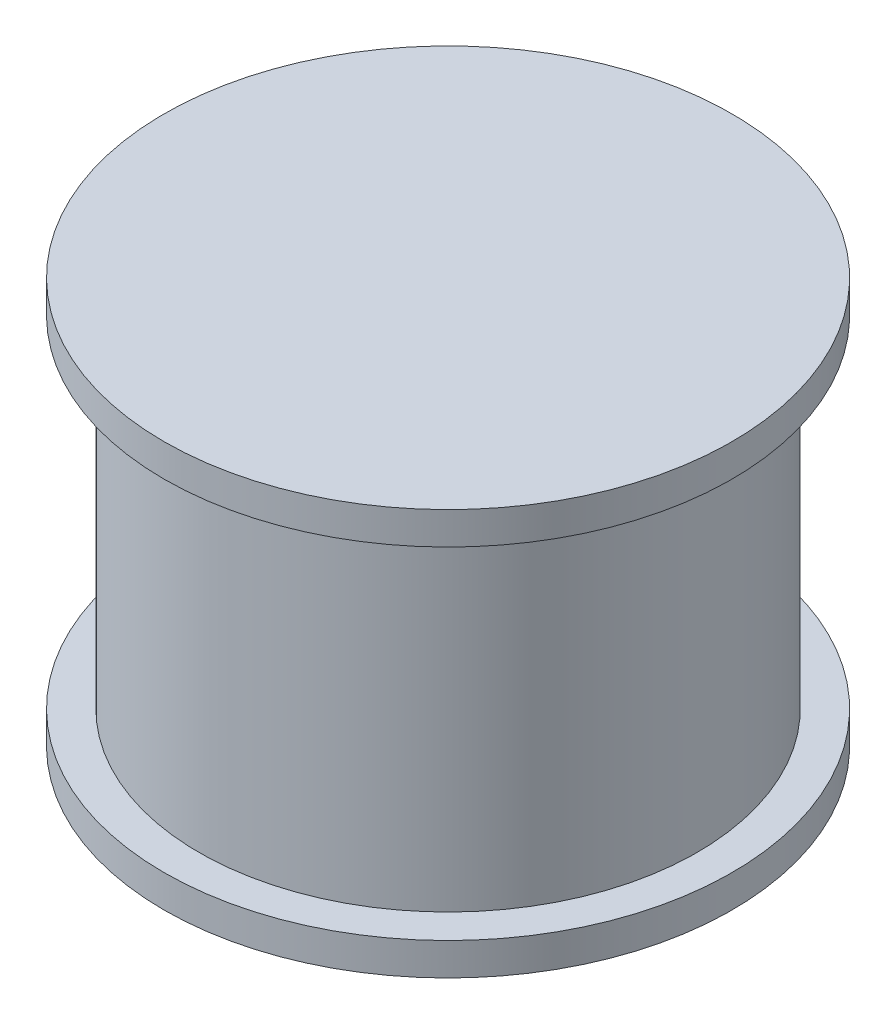
SolidWorks part; units mm, degrees
ref_plane "前视基准面" through (0, 0, 0) normal (0, 0, 1) x (1, 0, 0)
ref_plane "上视基准面" through (0, 0, 0) normal (0, 1, 0) x (1, 0, 0)
ref_plane "右视基准面" through (0, 0, 0) normal (1, 0, 0) x (0, 0, -1)
other "Configuration Table"
sketch "草图1" plane through (0, 0, 0) normal (0, 1, 0) x (1, 0, 0)
  circle A0 centre (0, 0) radius 15.35
  dimension "D1" = 30.7
extrude "凸台-拉伸1" add sketch "草图1" along normal mid plane 21
sketch "草图2" plane through (0, 10.5, 0) normal (0, 1, 0) x (1, 0, 0)
  circle A0 centre (0, 0) radius 17.5
  dimension "D1" = 35
extrude "凸台-拉伸2" add sketch "草图2" along normal blind 2
mirror "镜向1" about plane through (0, 0, 0) normal (0, 1, 0) of "凸台-拉伸2"
